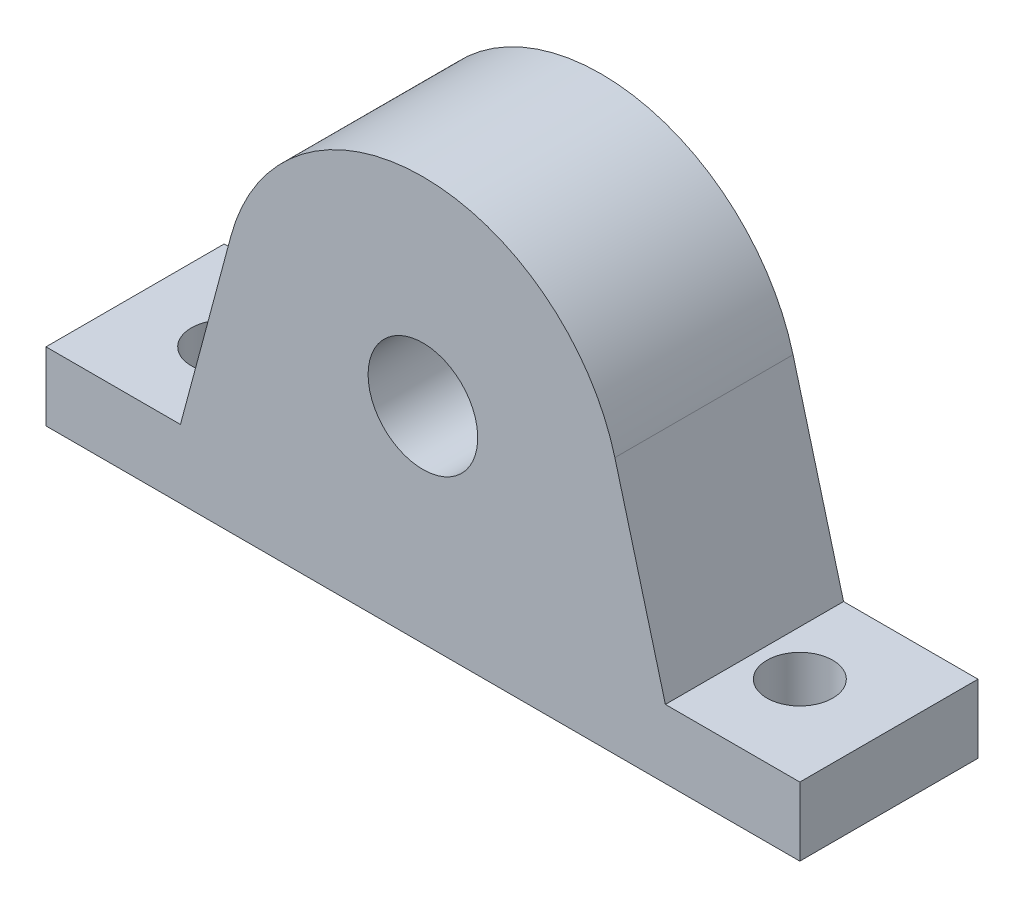
SolidWorks part; units mm, degrees
ref_plane "前视基准面" through (0, 0, 0) normal (0, 0, 1) x (1, 0, 0)
ref_plane "上视基准面" through (0, 0, 0) normal (0, 1, 0) x (1, 0, 0)
ref_plane "右视基准面" through (0, 0, 0) normal (1, 0, 0) x (0, 0, -1)
other "Configuration Table"
sketch "草图1" plane through (0, 0, 0) normal (0, 0, 1) x (1, 0, 0)
  line L0 (-27.5, 0) -> (27.5, 0)
  line L1 (27.5, 0) -> (27.5, 5)
  line L2 (27.5, 5) -> (17.691, 5)
  line L3 (-27.5, 5) -> (-27.5, 0)
  line L4 (-17.691, 5) -> (-27.5, 5)
  line L5 (0, 15) -> (0, 0) construction
  line L6 (-14.0059, 18.7529) -> (-17.691, 5)
  line L7 (14.0059, 18.7529) -> (17.691, 5)
  circle A0 centre (0, 15) radius 4
  arc A1 (14.0059, 18.7529) -> (-14.0059, 18.7529) centre (0, 15) ccw
  point P3 (0, 0)
  dimension "D3" = 8
  dimension "D4" = 29
  dimension "D1" = 55
  dimension "D2" = 5
  dimension "D5" = 15
  dimension "D6" = 15
extrude "凸台-拉伸1" add sketch "草图1" along normal mid plane 13
sketch "草图2" plane through (0, 5, 0) normal (0, 1, 0) x (1, 0, 0)
  line L0 (-21, 0) -> (0, 0) construction
  line L1 (0, 0) -> (0, 3.8356) construction
  circle A0 centre (-21, 0) radius 2.4
  circle A1 centre (21, 0) radius 2.4
  dimension "D2" = 4.8
  dimension "D1" = 21
extrude "切除-拉伸1" cut sketch "草图2" against normal blind 13
